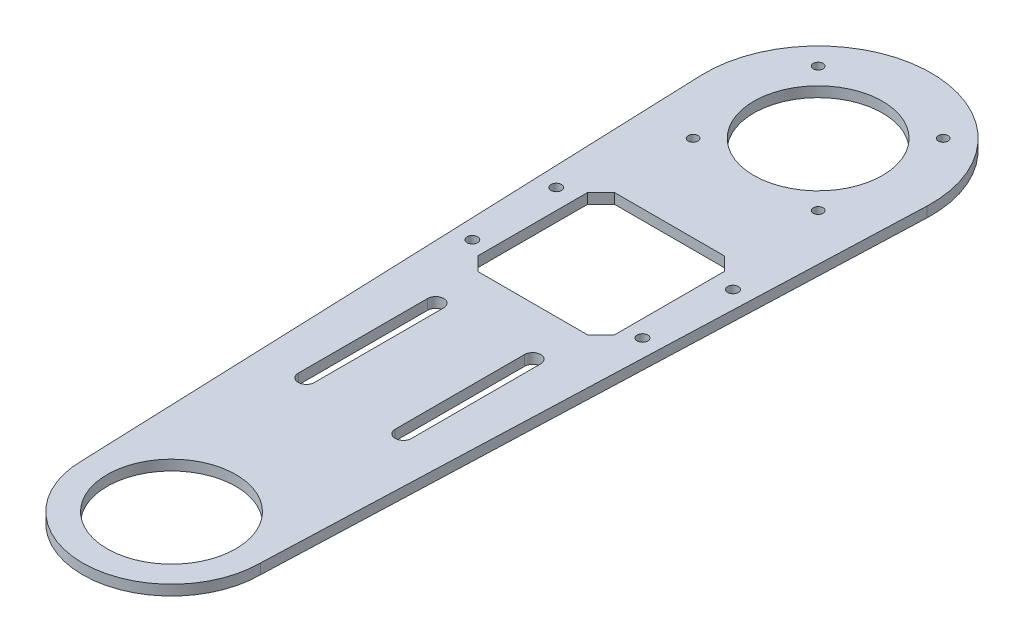
SolidWorks part; units mm, degrees
ref_plane "Front Plane" through (0, 0, 0) normal (0, 0, 1) x (1, 0, 0)
ref_plane "Top Plane" through (0, 0, 0) normal (0, 1, 0) x (1, 0, 0)
ref_plane "Right Plane" through (0, 0, 0) normal (1, 0, 0) x (0, 0, -1)
sketch "Sketch1" plane through (0, 0, 0) normal (0, 1, 0) x (1, 0, 0)
  line L0 (-27.5, -100) -> (-34.9753, 98.6841)
  line L1 (27.5, -100) -> (34.9753, 98.6841)
  arc A0 (-27.5, -100) -> (27.5, -100) centre (0, -100) ccw
  arc A2 (34.9753, 98.6841) -> (-34.9753, 98.6841) centre (0, 100) ccw
  dimension "D1" = 55
  dimension "D2" = 200
  dimension "D3" = 70
  dimension "D4" = 100
extrude "Boss-Extrude1" add sketch "Sketch1" along normal blind 3.175
sketch "Sketch2" plane through (0, 3.175, 0) normal (0, 1, 0) x (1, 0, 0)
  circle A0 centre (0, -100) radius 19.9
  circle A1 centre (0, 100) radius 19.9
  dimension "D1" = 39.8
  dimension "D2" = 200
  dimension "D3" = 100
extrude "Cut-Extrude1" cut sketch "Sketch2" against normal through all
sketch "Esquisse1" plane through (0, 3.175, 0) normal (0, 1, 0) x (1, 0, 0)
  circle A0 centre (0, 100) radius 27.35
  circle A2 centre (0, 100) radius 19.9 construction
  dimension "D1" = 54.7
sketch "Esquisse2" plane through (0, 3.175, 0) normal (0, 1, 0) x (1, 0, 0)
  line L0 (-19.3394, 80.6606) -> (19.3394, 80.6606) construction
  line L1 (19.3394, 80.6606) -> (19.3394, 119.3394) construction
  line L2 (19.3394, 119.3394) -> (-19.3394, 119.3394) construction
  line L3 (-19.3394, 119.3394) -> (-19.3394, 80.6606) construction
  circle A0 centre (19.3394, 80.6606) radius 1.5
  circle A2 centre (19.3394, 119.3394) radius 1.5
  circle A3 centre (-19.3394, 119.3394) radius 1.5
  circle A4 centre (-19.3394, 80.6606) radius 1.5
  circle A6 centre (0, 100) radius 27.35 construction
  point P2 (0, 80.6606)
  dimension "D1" = 3
extrude "Enlèv. mat.-Extru.1" cut sketch "Esquisse2" against normal through all
sketch "Sketch3" plane through (0, 3.175, 0) normal (0, 1, 0) x (1, 0, 0)
  circle A0 centre (0, 41.5664) radius 4.425
  dimension "D1" = 8.85
extrude "Cut-Extrude2" [suppressed] cut sketch "Sketch3" against normal through all
sketch "Sketch5" plane through (0, 3.175, 0) normal (0, 1, 0) x (1, 0, 0)
  line L0 (-21.15, 49.8281) -> (-16.9781, 54)
  line L1 (-16.9781, 54) -> (16.9781, 54)
  line L2 (16.9781, 54) -> (21.15, 49.8281)
  line L3 (21.15, 49.8281) -> (21.15, 15.8719)
  line L4 (21.15, 15.8719) -> (16.9781, 11.7)
  line L5 (16.9781, 11.7) -> (-16.9781, 11.7)
  line L6 (-16.9781, 11.7) -> (-21.15, 15.8719)
  line L7 (-21.15, 15.8719) -> (-21.15, 49.8281)
  circle A0 centre (-27.3317, 46.3405) radius 1.625
  circle A1 centre (-26.3166, 19.3595) radius 1.625
  circle A2 centre (26.3166, 19.3595) radius 1.625
  circle A3 centre (27.3317, 46.3405) radius 1.625
  dimension "D1" = 3.25
extrude "Cut-Extrude3" cut sketch "Sketch5" against normal through all
sketch "Sketch7" plane through (0, 3.175, 0) normal (0, 1, 0) x (1, 0, 0)
  line L0 (17.5, -43.3) -> (17.5, -3.3)
  line L3 (12.5, -3.3) -> (12.5, -43.3)
  line L7 (-12.5, -43.3) -> (-12.5, -3.3)
  line L8 (-17.5, -3.3) -> (-17.5, -43.3)
  arc A4 (17.5, -3.3) -> (12.5, -3.3) centre (15, -3.3) ccw
  arc A5 (12.5, -43.3) -> (17.5, -43.3) centre (15, -43.3) ccw
  arc A6 (-12.5, -3.3) -> (-17.5, -3.3) centre (-15, -3.3) ccw
  arc A7 (-17.5, -43.3) -> (-12.5, -43.3) centre (-15, -43.3) ccw
extrude "Cut-Extrude4" cut sketch "Sketch7" against normal through all
